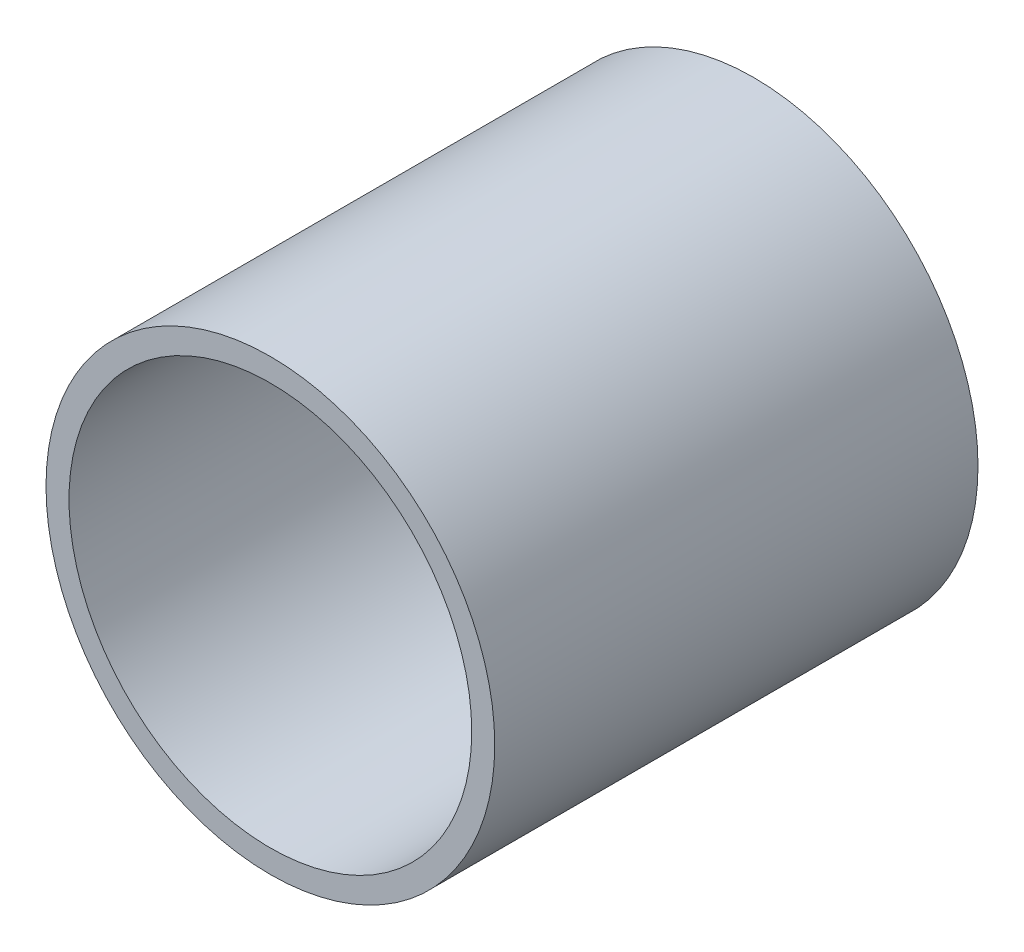
SolidWorks part; units mm, degrees
ref_plane "Front Plane" through (0, 0, 0) normal (0, 0, 1) x (1, 0, 0)
ref_plane "Top Plane" through (0, 0, 0) normal (0, 1, 0) x (1, 0, 0)
ref_plane "Right Plane" through (0, 0, 0) normal (1, 0, 0) x (0, 0, -1)
sketch "Sketch1" plane through (0, 0, 0) normal (0, 0, 1) x (1, 0, 0)
  circle A0 centre (0, 0) radius 1.75
  circle A1 centre (0, 0) radius 1.95
  dimension "D1" = 3.9
  dimension "D2" = 0.2
extrude "Boss-Extrude1" add sketch "Sketch1" along normal blind 4.2
